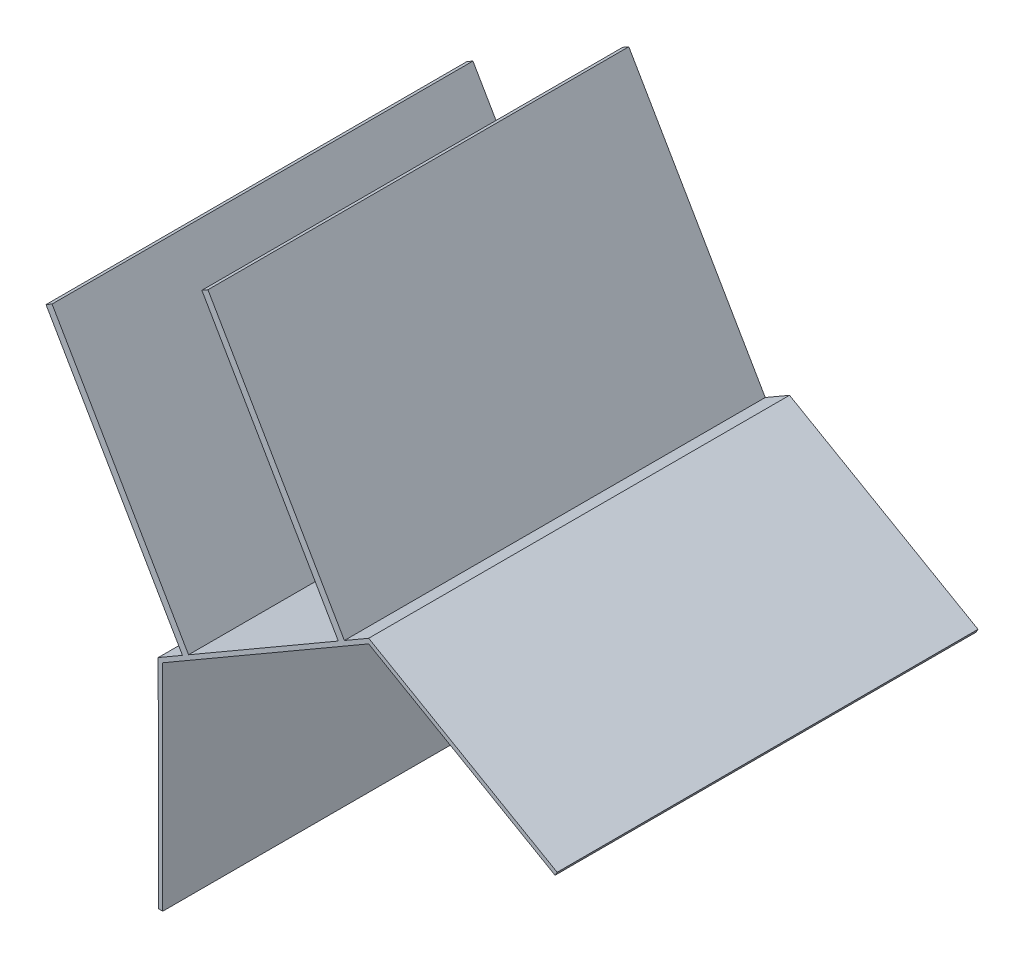
SolidWorks part; units mm, degrees
ref_plane "Front Plane" through (0, 0, 0) normal (0, 0, 1) x (1, 0, 0)
ref_plane "Top Plane" through (0, 0, 0) normal (0, 1, 0) x (1, 0, 0)
ref_plane "Right Plane" through (0, 0, 0) normal (1, 0, 0) x (0, 0, -1)
sketch "Sketch1" plane through (0, 0, 0) normal (0, 0, 1) x (1, 0, 0)
  line L0 (1528.9664, 0) -> (0, 0) construction
  line L1 (0, 0) -> (-918.1607, 1590.301) construction
  line L2 (0, 0) -> (-694.8278, -1203.4771) construction
  line L3 (0, 0) -> (-1542.2771, 0) construction
  line L4 (0, 0) -> (625.4451, 1083.3028) construction
  line L5 (0, 0) -> (646.494, -1119.7604) construction
  line L6 (-1000, 0) -> (-502.6514, 864.4892)
  line L7 (-502.6514, 864.4892) -> (502.6514, 864.4892)
  line L8 (502.6514, 864.4892) -> (1000, 0)
  line L9 (1000, 0) -> (500, -866.0254)
  line L10 (500, -866.0254) -> (-500, -866.0254)
  line L11 (-500, -866.0254) -> (-1000, 0)
  line L12 (1224.9953, 228.0643) -> (1224.9953, -221.9357)
  line L13 (-810.0072, 946.8449) -> (-420.2957, 1171.8449)
  line L14 (-810.0072, 946.8449) -> (-585.0072, 557.1335)
  line L15 (-585.0072, 557.1335) -> (-195.2957, 782.1335)
  line L16 (-420.2957, 1171.8449) -> (-195.2957, 782.1335)
  line L17 (-810.0072, 946.8449) -> (-195.2957, 782.1335) construction
  line L18 (-585.0072, 557.1335) -> (-420.2957, 1171.8449) construction
  line L19 (-500, -866.0254) -> (-502.6514, 864.4892)
  line L20 (-502.6514, 864.4892) -> (1000, 0)
  line L21 (1000, 0) -> (-500, -866.0254)
  line L22 (-599.9999, -866.1786) -> (-602.6563, 867.5995)
  line L23 (-946.6097, 983.4474) -> (-58.6932, 745.5309) construction
  line L24 (-455.6168, 952.7978) -> (1049.8673, 86.679)
  line L25 (1050, -86.6025) -> (-450, -952.6279)
  line L26 (-602.6513, 864.336) -> (-502.6514, 864.4892)
  line L27 (1224.9953, -221.9357) -> (774.9953, -221.9357)
  line L28 (774.9953, 228.0643) -> (774.9953, -221.9357)
  line L29 (-452.7842, 951.1682) -> (-502.6514, 864.4892)
  line L30 (1224.9953, 228.0643) -> (774.9953, 228.0643)
  line L31 (1049.8673, 86.679) -> (1000, 0)
  line L32 (-414.9882, -1174.9092) -> (-804.6996, -949.9092)
  line L33 (1000, 0) -> (1050, -86.6025)
  line L34 (-450, -952.6279) -> (-500, -866.0254)
  line L35 (-804.6996, -949.9092) -> (-579.6996, -560.1978)
  line L36 (-189.9882, -785.1978) -> (-579.6996, -560.1978)
  line L37 (-599.9999, -866.1786) -> (-500, -866.0254)
  line L38 (-414.9882, -1174.9092) -> (-189.9882, -785.1978)
  line L39 (-602.9953, -869.1832) -> (-499.9954, -869.0254)
  line L40 (-602.9999, -866.1832) -> (-605.659, 869.3269)
  line L41 (-602.9999, -866.1832) -> (-605.6513, 864.3314) construction
  line L42 (-451.2882, 953.7686) -> (1051.3633, 89.2794)
  line L43 (-602.9953, -869.1832) -> (-605.6559, 867.3314) construction
  line L44 (-605.6559, 867.3314) -> (-502.656, 867.4892) construction
  line L45 (-451.2882, 953.7686) -> (-455.6221, 956.262)
  line L46 (-605.659, 869.3269) -> (-455.6221, 956.262)
  line L47 (-602.6563, 867.5995) -> (-455.6168, 952.7978)
  line L48 (-602.4215, 714.3314) -> (-605.4215, 714.3314)
  line L49 (-322.7656, 876.3673) -> (-321.2696, 878.9677)
  line L50 (-599.9999, -866.1786) -> (-602.6513, 864.336) construction
  line L51 (-452.7842, 951.1682) -> (1049.8673, 86.679) construction
  line L52 (-604.1473, 866.7356) -> (-454.1181, 953.6662) construction
  line L53 (-605.6513, 869.3314) -> (-455.6221, 956.262) construction
  circle A0 centre (0, 0) radius 750 construction
  circle A1 centre (0, 0) radius 1000 construction
  point P31 (0, 0)
  point P32 (-18.2945, 0.0494)
  point P45 (0, 0)
  dimension "D1" = 1500
  dimension "D2" = 2000
  dimension "D3" = 120
  dimension "D4" = 1005.3029
  dimension "D5" = 60
  dimension "D6" = 60
  dimension "D7" = 60
  dimension "D8" = 450
  dimension "D9" = 100
  dimension "D11" = 60
  dimension "D12" = 3
  dimension "D10" = 3
  dimension "D14" = 3
  dimension "D17" = 150
  dimension "D18" = 3
  dimension "D13" = 3
extrude "Boss-Extrude3" add sketch "Sketch1" along normal mid plane 300
sketch "Sketch3" plane through (-529.3341, 913.5514, 0) normal (-0.5013, 0.8652, 0) x (0.8652, 0.5013, 0)
  line L0 (-88.2116, -150) -> (85.1918, -150) construction
  line L1 (65.1918, 150) -> (60.1918, 150)
  line L2 (65.1918, 150) -> (65.1918, -150)
  line L3 (65.1918, -150) -> (60.1918, -150)
  line L4 (60.1918, 150) -> (60.1918, -150)
  line L5 (85.1918, -150) -> (85.1918, 150) construction
  line L6 (-68.2116, 150) -> (-63.2116, 150)
  line L7 (-68.2116, 150) -> (-68.2116, -150)
  line L8 (-68.2116, -150) -> (-63.2116, -150)
  line L9 (-63.2116, 150) -> (-63.2116, -150)
  line L10 (-88.2116, -150) -> (-88.2116, 150) construction
  dimension "D1" = 5
  dimension "D2" = 20
  dimension "D3" = 20
extrude "Boss-Extrude4" add sketch "Sketch3" along normal blind 194.04
